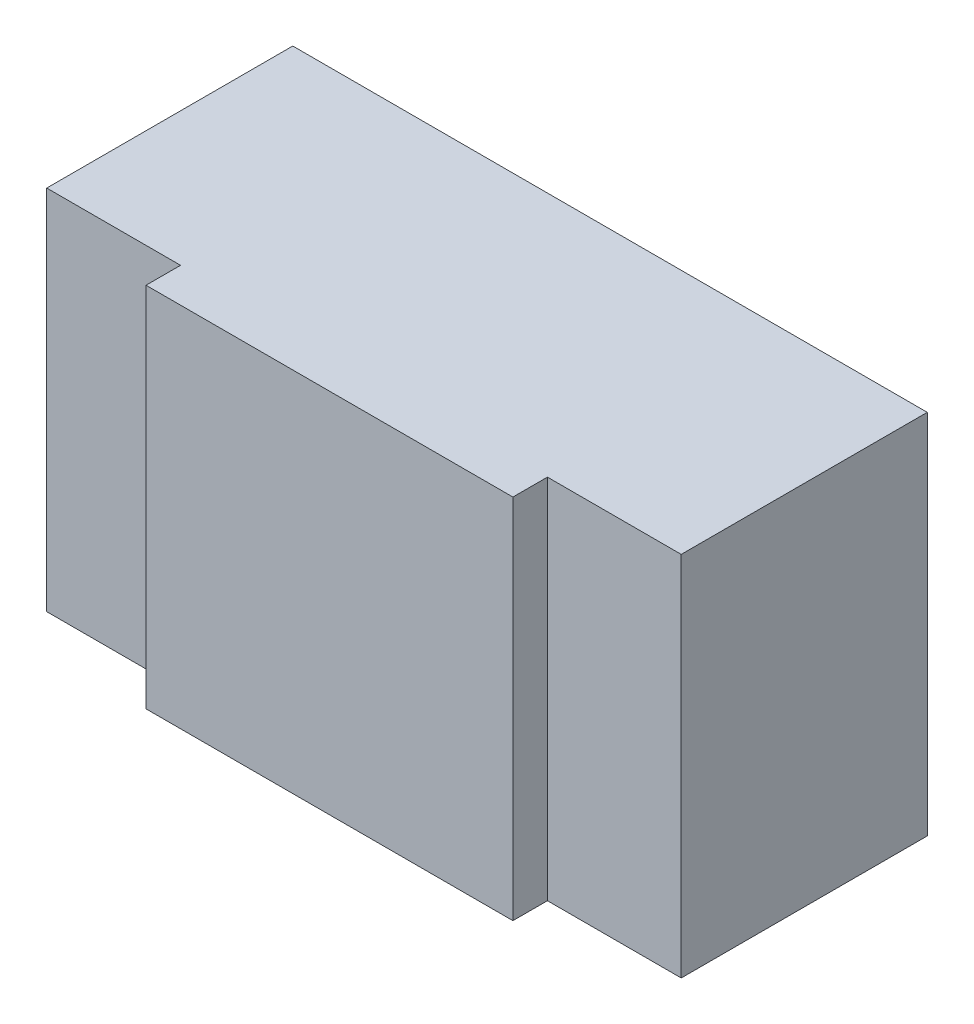
SolidWorks part; units mm, degrees
ref_plane "Front Plane" through (0, 0, 0) normal (0, 0, 1) x (1, 0, 0)
ref_plane "Top Plane" through (0, 0, 0) normal (0, 1, 0) x (1, 0, 0)
ref_plane "Right Plane" through (0, 0, 0) normal (1, 0, 0) x (0, 0, -1)
sketch "Sketch1" plane through (0, 0, 0) normal (0, 0, 1) x (1, 0, 0)
  line L1 (-73.5, -42.5) -> (73.5, -42.5)
  line L2 (-73.5, -42.5) -> (-73.5, 42.5)
  line L3 (-73.5, 42.5) -> (73.5, 42.5)
  line L4 (73.5, -42.5) -> (73.5, 42.5)
  line L5 (-73.5, -42.5) -> (73.5, 42.5) construction
  line L6 (-73.5, 42.5) -> (73.5, -42.5) construction
  point P0 (0, 0)
  dimension "D1" = 147
  dimension "D2" = 85
extrude "Boss-Extrude1" add sketch "Sketch1" along normal blind 57
sketch "Sketch2" plane through (0, 0, 57) normal (0, 0, 1) x (1, 0, 0)
  line L0 (73.5, 42.5) -> (-73.5, 42.5) construction
  line L1 (-42.5, 42.5) -> (42.5, 42.5)
  line L2 (-42.5, 42.5) -> (-42.5, -42.5)
  line L3 (-42.5, -42.5) -> (42.5, -42.5)
  line L4 (42.5, 42.5) -> (42.5, -42.5)
  line L5 (-73.5, -42.5) -> (73.5, -42.5) construction
  line L6 (-73.5, 42.5) -> (-73.5, -42.5) construction
  dimension "D1" = 31
  dimension "D2" = 85
extrude "Boss-Extrude2" add sketch "Sketch2" along normal blind 8
sketch "Sketch3" plane through (-73.5, 0, 0) normal (-1, 0, 0) x (0, 0, 1)
  line L1 (30, -4.5) -> (54, -4.5)
  line L2 (30, -4.5) -> (30, -35.5)
  line L3 (30, -35.5) -> (54, -35.5)
  line L4 (54, -4.5) -> (54, -35.5)
  line L6 (57, 42.5) -> (57, -42.5) construction
  line L7 (57, -42.5) -> (0, -42.5) construction
  dimension "D1" = 3
  dimension "D2" = 24
  dimension "D3" = 31
  dimension "D4" = 7
extrude "Boss-Extrude3" add sketch "Sketch3" along normal blind 1
